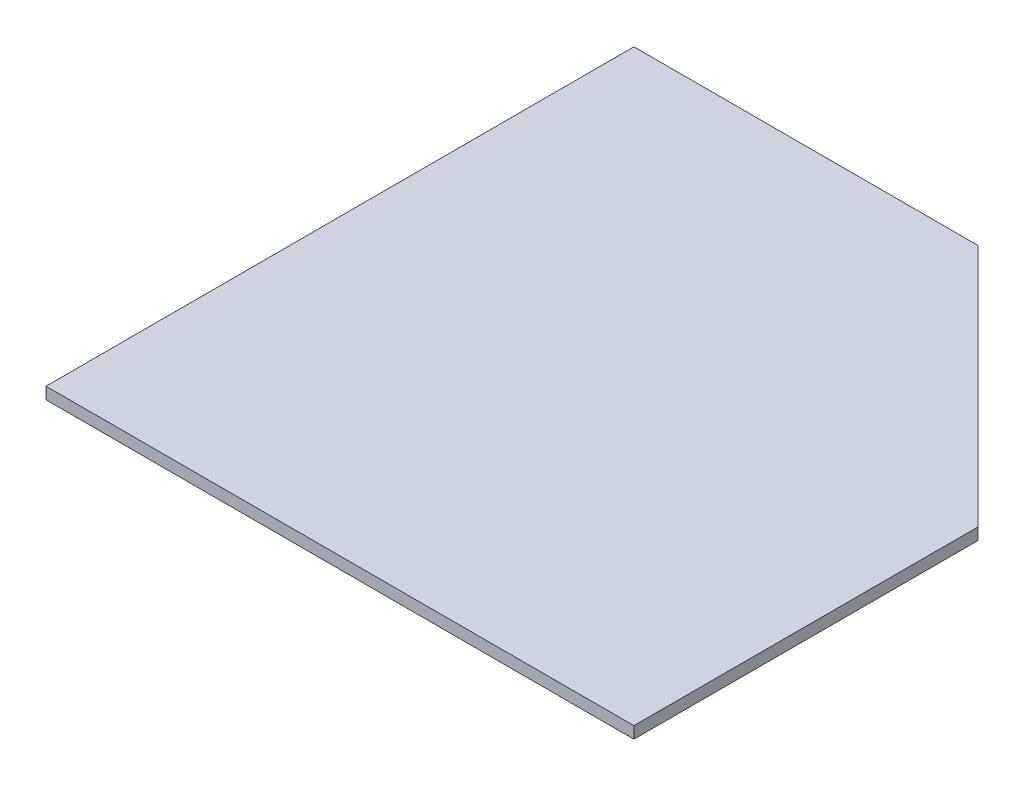
SolidWorks part; units mm, degrees
material "Ст 3 ГОСТ 380-88"
ref_plane "Спереди" through (0, 0, 0) normal (0, 0, 1) x (1, 0, 0)
ref_plane "Сверху" through (0, 0, 0) normal (0, 1, 0) x (1, 0, 0)
ref_plane "Справа" through (0, 0, 0) normal (1, 0, 0) x (0, 0, -1)
sketch "Sketch1" plane through (0, 0, 0) normal (0, 1, 0) x (1, 0, 0)
  line L1 (-100, 100) -> (100, 100)
  line L2 (-100, 100) -> (-100, -100)
  line L3 (-100, -100) -> (100, -100)
  line L4 (100, 100) -> (100, -100)
  line L5 (-100, 100) -> (100, -100) construction
  line L6 (-100, -100) -> (100, 100) construction
  point P0 (0, 0)
  dimension "D1" = 200
  dimension "D2" = 200
extrude "Boss-Extrude1" add sketch "Sketch1" along normal blind 4
sketch "Sketch2" plane through (0, 4, 0) normal (0, 1, 0) x (1, 0, 0)
  line L0 (213.3757, -85) -> (-85, 213.3757) construction
  line L2 (215.0179, -85) -> (-85, 215.0179) construction
  line L3 (213.3757, -85) -> (-85, 213.3757) construction
  line L4 (207.7189, -90.6569) -> (-90.6569, 207.7189)
  dimension "D1" = 8
extrude "Cut-Extrude1" cut sketch "Sketch2" against normal through all and the other way through all flip side to cut
